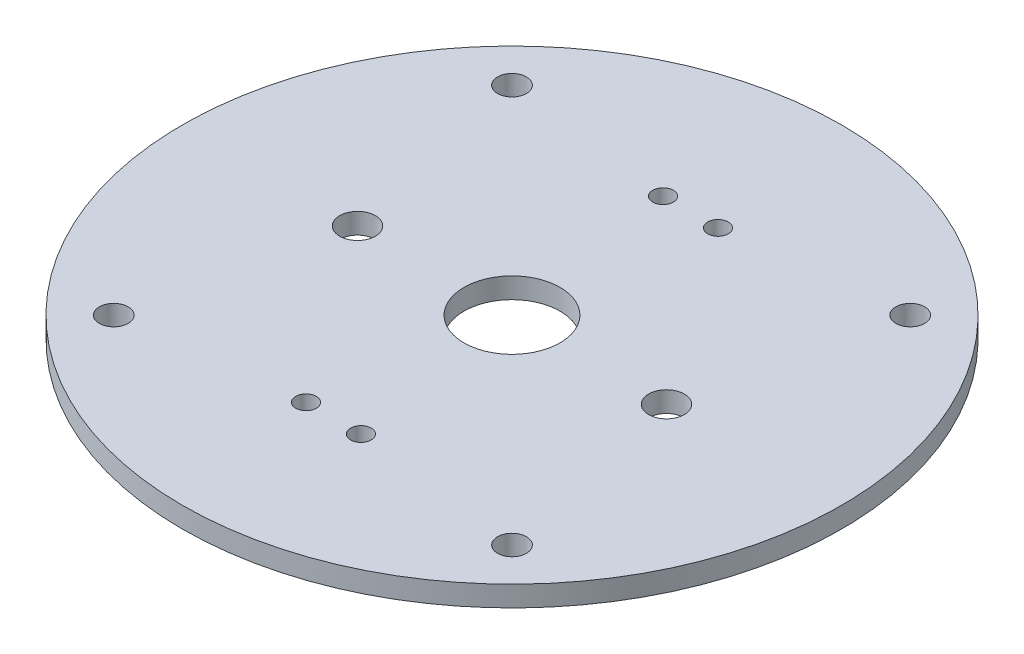
SolidWorks part; units mm, degrees
ref_plane "前视基准面" through (0, 0, 0) normal (0, 0, 1) x (1, 0, 0)
ref_plane "上视基准面" through (0, 0, 0) normal (0, 1, 0) x (1, 0, 0)
ref_plane "右视基准面" through (0, 0, 0) normal (1, 0, 0) x (0, 0, -1)
other "Configuration Table"
sketch "草图1" plane through (0, 0, 0) normal (0, 1, 0) x (1, 0, 0)
  line L1 (-29, -29) -> (29, -29) construction
  line L2 (-29, -29) -> (-29, 29) construction
  line L3 (-29, 29) -> (29, 29) construction
  line L4 (29, -29) -> (29, 29) construction
  line L5 (-29, -29) -> (29, 29) construction
  line L6 (-29, 29) -> (29, -29) construction
  circle A0 centre (0, 0) radius 48
  circle A1 centre (-29, 29) radius 2.1
  circle A2 centre (29, 29) radius 2.1
  circle A3 centre (29, -29) radius 2.1
  circle A4 centre (-29, -29) radius 2.1
  dimension "D1" = 96
  dimension "D4" = 4.2
  dimension "D5" = 4.2
  dimension "D6" = 4.2
  dimension "D7" = 4.2
  dimension "D2" = 58
  dimension "D3" = 58
extrude "凸台-拉伸1" add sketch "草图1" along normal blind 3
sketch "草图2" plane through (0, 3, 0) normal (0, 1, 0) x (1, 0, 0)
  line L0 (-64.0525, 0) -> (61.5676, 0) construction
  circle A0 centre (0, 0) radius 7
  circle A1 centre (0, 0) radius 22.5 construction
  circle A2 centre (-22.5, 0) radius 2.6
  circle A3 centre (22.5, 0) radius 2.6
  dimension "D1" = 14
  dimension "D2" = 45
  dimension "D3" = 5.2
  dimension "D4" = 5.2
extrude "切除-拉伸1" cut sketch "草图2" against normal through all
sketch "草图3" plane through (0, 3, 0) normal (0, 1, 0) x (1, 0, 0)
  line L0 (-29, 29) -> (29, 29) construction
  line L1 (-29, -29) -> (29, -29) construction
  line L2 (0, 29) -> (0, -29) construction
  line L3 (-4, 26) -> (4, 26) construction
  line L4 (-4, -26) -> (4, -26) construction
  line L5 (-22.5, 0) -> (22.5, 0) construction
  circle A0 centre (4, 26) radius 1.5
  circle A1 centre (-4, 26) radius 1.5
  circle A2 centre (-4, -26) radius 1.5
  circle A3 centre (4, -26) radius 1.5
  point P18 (0, 26)
  point P19 (0, -26)
  dimension "D2" = 3
  dimension "D1" = 52
  dimension "D3" = 8
  dimension "D4" = 8
extrude "切除-拉伸2" cut sketch "草图3" against normal blind 10
